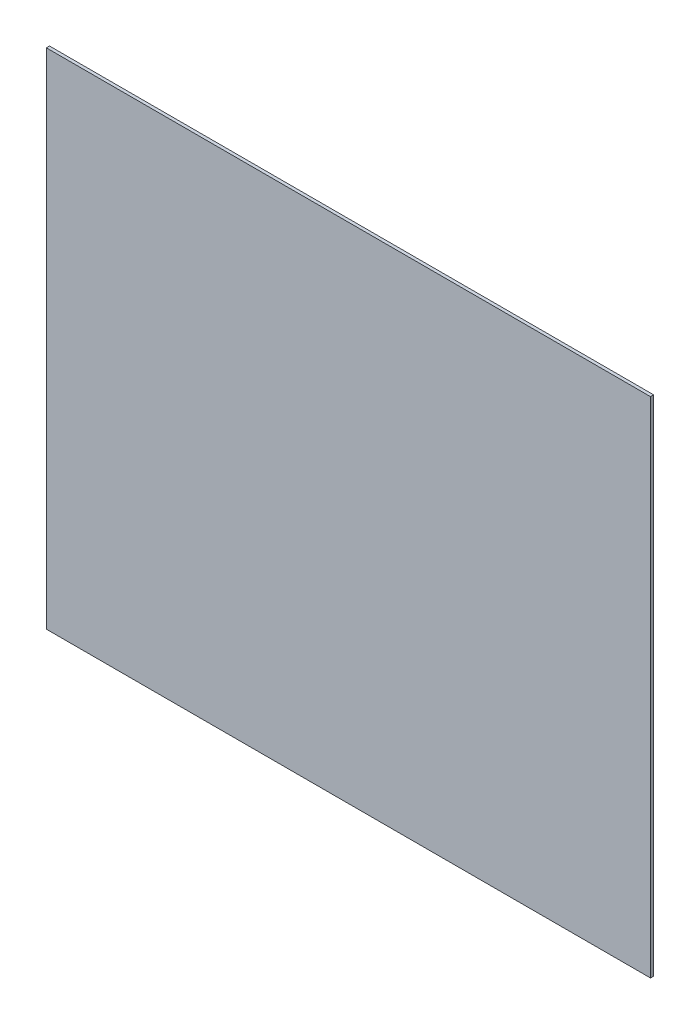
SolidWorks part; units mm, degrees
material "1060 Alloy"
ref_plane "Front Plane" through (0, 0, 0) normal (0, 0, 1) x (1, 0, 0)
ref_plane "Top Plane" through (0, 0, 0) normal (0, 1, 0) x (1, 0, 0)
ref_plane "Right Plane" through (0, 0, 0) normal (1, 0, 0) x (0, 0, -1)
sketch "Sketch1" plane through (0, 0, 0) normal (0, 0, 1) x (1, 0, 0)
  line L1 (-304.8, -254) -> (304.8, -254)
  line L2 (-304.8, -254) -> (-304.8, 254)
  line L3 (-304.8, 254) -> (304.8, 254)
  line L4 (304.8, -254) -> (304.8, 254)
  line L5 (-304.8, -254) -> (304.8, 254) construction
  line L6 (-304.8, 254) -> (304.8, -254) construction
  point P0 (0, 0)
  dimension "D1" = 609.6
  dimension "D2" = 508
extrude "Boss-Extrude1" add sketch "Sketch1" along normal blind 3.175
